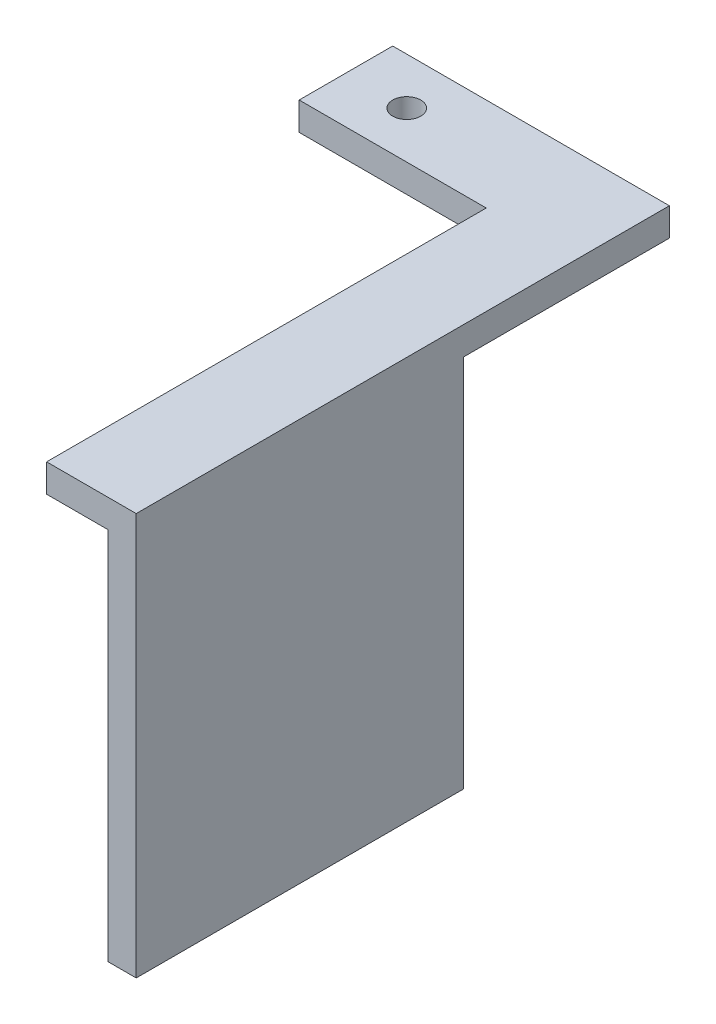
SolidWorks part; units mm, degrees
material "Perspex (TM) GS Acrylic Cast Sheet"
ref_plane "Front Plane" through (0, 0, 0) normal (0, 0, 1) x (1, 0, 0)
ref_plane "Top Plane" through (0, 0, 0) normal (0, 1, 0) x (1, 0, 0)
ref_plane "Right Plane" through (0, 0, 0) normal (1, 0, 0) x (0, 0, -1)
sketch "Sketch1" plane through (0, 0, 0) normal (0, 1, 0) x (1, 0, 0)
  line L0 (10, -5) -> (10, -52)
  line L1 (10, -5) -> (-10, -5)
  line L3 (10, 5) -> (-10, 5)
  line L4 (-10, -5) -> (-10, 5)
  line L5 (10, -5) -> (-10, 5) construction
  line L6 (10, 5) -> (-10, -5) construction
  line L7 (10, -52) -> (19.5785, -52)
  line L8 (19.5785, -52) -> (19.5785, 5)
  line L9 (19.5785, 5) -> (10, 5)
  point P0 (0, 0)
  dimension "D1" = 10
  dimension "D2" = 10
  dimension "D3" = 19.5785
  dimension "D4" = 52
extrude "Boss-Extrude1" add sketch "Sketch1" along normal blind 3
sketch "Sketch2" plane through (0, 3, 0) normal (0, 1, 0) x (1, 0, 0)
  line L0 (-10, -5) -> (10, -5) construction
  line L1 (-10, 5) -> (-10, -5) construction
  circle A0 centre (-3.5, 0) radius 1.5
  dimension "D1" = 3
  dimension "D2" = 5
  dimension "D3" = 6.5
extrude "Cut-Extrude1" cut sketch "Sketch2" against normal blind 3
sketch "Sketch3" plane through (0, 0, 0) normal (0, -1, 0) x (1, 0, 0)
  line L0 (19.5785, 52) -> (19.5785, -5) construction
  line L1 (19.5785, 17) -> (16.5785, 17)
  line L2 (19.5785, 17) -> (19.5785, 52)
  line L3 (19.5785, 52) -> (16.5785, 52)
  line L4 (16.5785, 17) -> (16.5785, 52)
  line L5 (19.5785, 17) -> (16.5785, 52) construction
  line L6 (19.5785, 52) -> (16.5785, 17) construction
  line L7 (10, 52) -> (19.5785, 52) construction
  point P0 (18.0785, 34.5)
  dimension "D1" = 35
  dimension "D2" = 3
  dimension "D3" = 0
  dimension "5" = 0
extrude "Boss-Extrude2" add sketch "Sketch3" along normal blind 40
